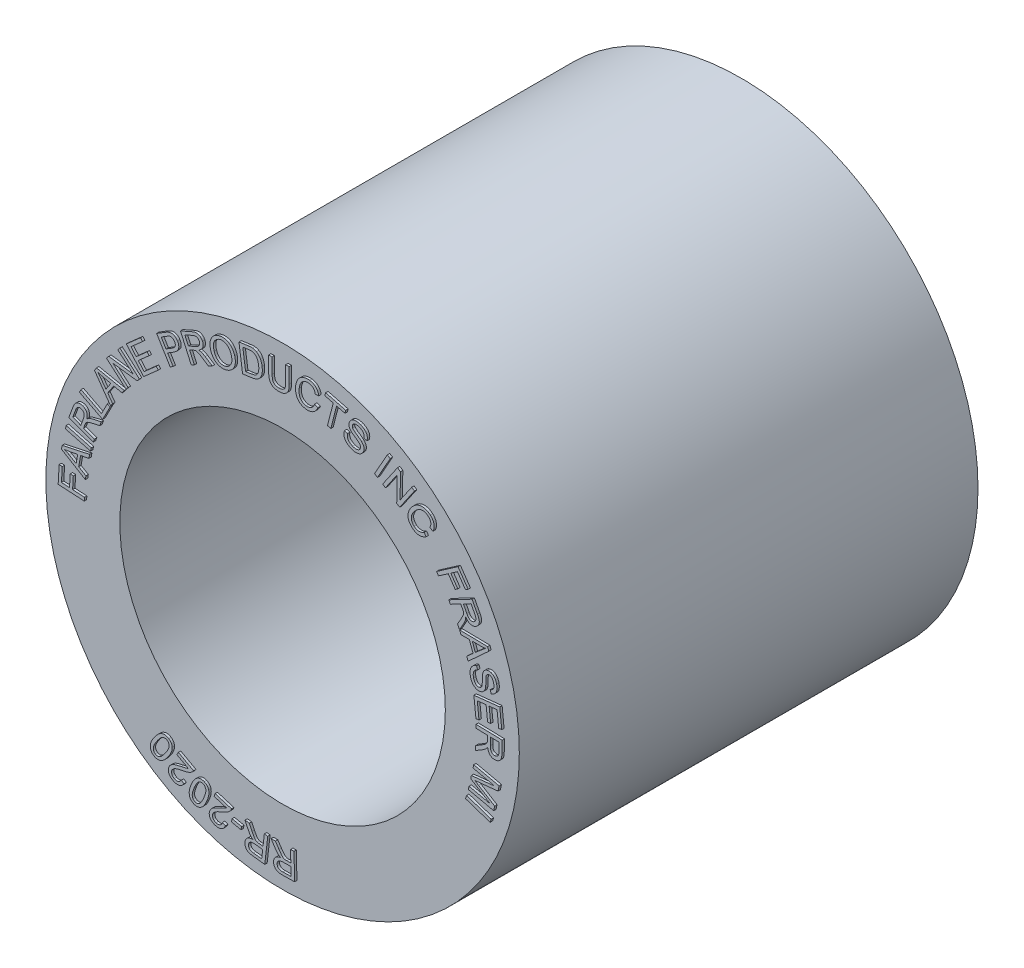
SolidWorks part; units mm, degrees
ref_plane "Front" through (0, 0, 0) normal (0, 0, 1) x (1, 0, 0)
ref_plane "Top" through (0, 0, 0) normal (0, 1, 0) x (1, 0, 0)
ref_plane "Right" through (0, 0, 0) normal (1, 0, 0) x (0, 0, -1)
sketch "Sketch1" plane through (0, 0, 0) normal (0, 0, 1) x (1, 0, 0)
  circle A0 centre (0, 0) radius 25.4
  dimension "D1" = 50.8
extrude "Base-Extrude" add sketch "Sketch1" along normal blind 49.2125
sketch "Sketch2" plane through (0, 0, 49.2125) normal (0, 0, 1) x (1, 0, 0)
  circle A0 centre (0, 0) radius 17.4625
  dimension "D1" = 34.925
extrude "Cut-Extrude1" cut sketch "Sketch2" against normal through all
sketch "Sketch4" plane through (0, 0, 49.2125) normal (0, 0, -1) x (-1, 0, 0)
  circle A0 centre (0, 0) radius 21.0407 construction
  text T0 "FAIRLANE PRODUCTS INC  FRASER MI                      RR-2020" font "Arial" height in points 11
  dimension "D1" = 42.0814
extrude "Extrude1" add sketch "Sketch4" against normal blind 0.254 separate body
